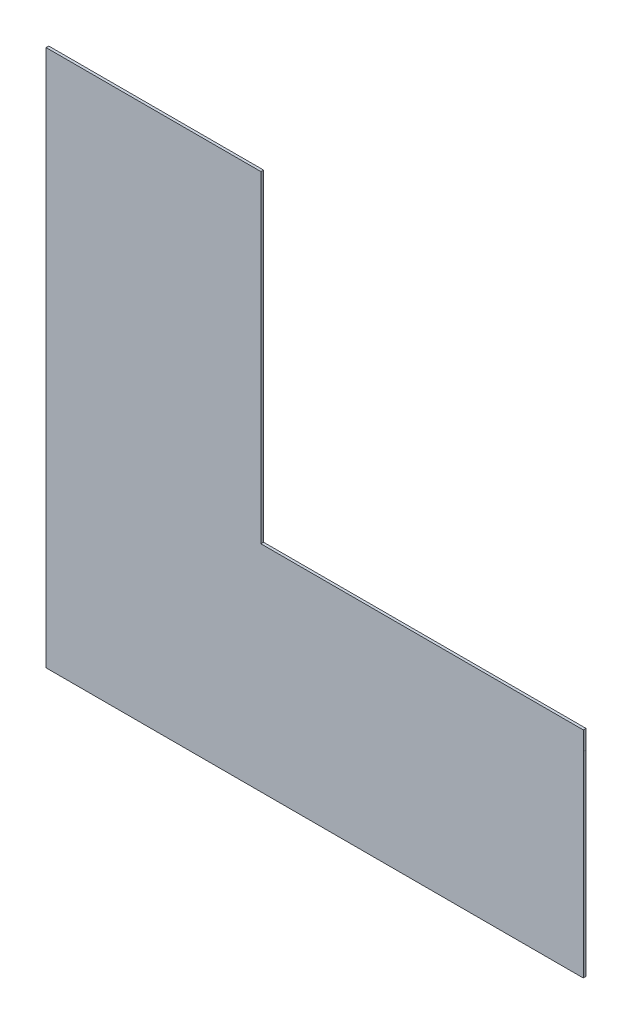
SolidWorks part; units mm, degrees
ref_plane "Front Plane" through (0, 0, 0) normal (0, 0, 1) x (1, 0, 0)
ref_plane "Top Plane" through (0, 0, 0) normal (0, 1, 0) x (1, 0, 0)
ref_plane "Right Plane" through (0, 0, 0) normal (1, 0, 0) x (0, 0, -1)
sketch "Sketch1" plane through (0, 0, 0) normal (0, 0, 1) x (1, 0, 0)
  line L0 (0, 0) -> (200, 0)
  line L1 (200, 0) -> (200, 80)
  line L2 (200, 80) -> (80, 80)
  line L3 (80, 80) -> (80, 200)
  line L4 (80, 200) -> (0, 200)
  line L5 (0, 200) -> (0, 0)
  dimension "D1" = 200
  dimension "D2" = 120
  dimension "D3" = 80
  dimension "D4" = 200
extrude "Boss-Extrude1" add sketch "Sketch1" along normal blind 1
ref_plane "Plane1" through (200, 0, 0) normal (1, 0, 0) x (0, 0, -1)
sketch "Sketch5" plane through (200, 0, 0) normal (1, 0, 0) x (0, 0, -1)
  line L0 (0, 0) -> (0, 80) construction
  line L1 (-1, 80) -> (0, 80)
  line L2 (-1, 80) -> (-1, 73)
  line L3 (-1, 73) -> (0, 73)
  line L4 (0, 80) -> (0, 73)
  line L5 (-1, 0) -> (0, 0) construction
  dimension "D1" = 7
  dimension "D2" = 73
split line "Split Line3"
